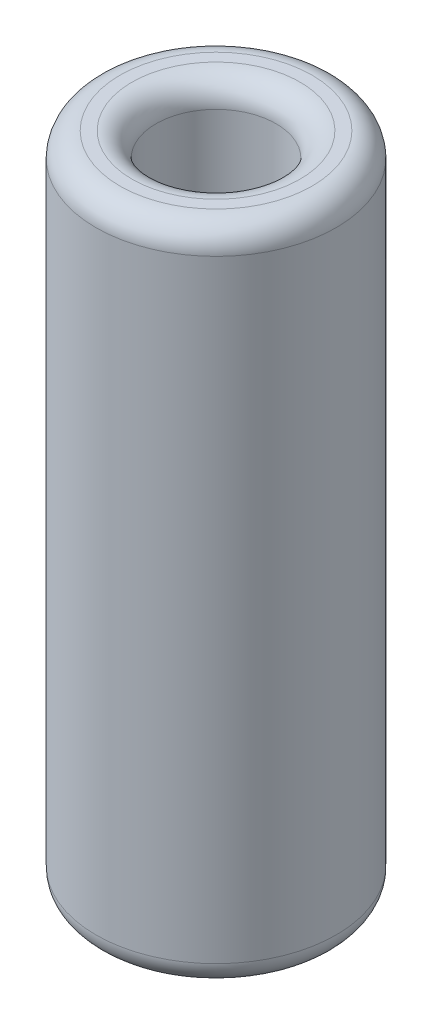
SolidWorks part; units mm, degrees
ref_plane "Front Plane" through (0, 0, 0) normal (0, 0, 1) x (1, 0, 0)
ref_plane "Top Plane" through (0, 0, 0) normal (0, 1, 0) x (1, 0, 0)
ref_plane "Right Plane" through (0, 0, 0) normal (1, 0, 0) x (0, 0, -1)
sketch "Sketch1" plane through (0, 0, 0) normal (0, 1, 0) x (1, 0, 0)
  circle A0 centre (0, 0) radius 12.7
  circle A1 centre (0, 0) radius 6.35
  dimension "D1" = 25.4
  dimension "D2" = 12.7
extrude "Boss-Extrude1" add sketch "Sketch1" along normal mid plane 69.85 contours A0
fillet "Fillet1" radius 2.54 4 edges at (0, -34.925, 6.35) (0, -34.925, 12.7) (0, 34.925, 6.35) (0, 34.925, 12.7)
